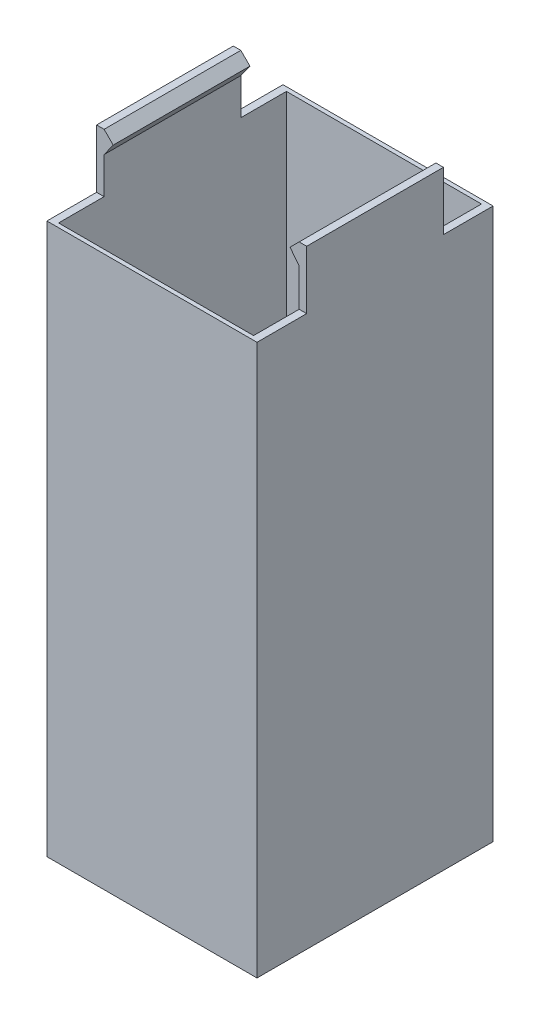
SolidWorks part; units mm, degrees
ref_plane "Front Plane" through (0, 0, 0) normal (0, 0, 1) x (1, 0, 0)
ref_plane "Top Plane" through (0, 0, 0) normal (0, 1, 0) x (1, 0, 0)
ref_plane "Right Plane" through (0, 0, 0) normal (1, 0, 0) x (0, 0, -1)
sketch "Sketch1" plane through (0, 0, 0) normal (0, 1, 0) x (1, 0, 0)
  line L0 (-23.05, 25.9) -> (42.3707, 25.9) construction
  line L1 (-23.05, 25.9) -> (23.05, 25.9)
  line L2 (-23.05, 25.9) -> (-23.05, -25.9)
  line L3 (-23.05, -25.9) -> (23.05, -25.9)
  line L4 (23.05, 25.9) -> (23.05, -25.9)
  line L5 (-23.05, 25.9) -> (23.05, -25.9) construction
  line L6 (-23.05, -25.9) -> (23.05, 25.9) construction
  line L7 (21.4, 25) -> (-21.4, 25)
  line L8 (21.4, 25) -> (21.4, -25)
  line L9 (21.4, -25) -> (-21.4, -25)
  line L10 (-21.4, 25) -> (-21.4, -25)
  line L11 (21.4, 25) -> (-21.4, -25) construction
  line L12 (21.4, -25) -> (-21.4, 25) construction
  point P0 (0, 0)
  point P6 (0, 0)
  dimension "D1" = 42.8
  dimension "D2" = 50
  dimension "D3" = 1.65
  dimension "D5" = 0.9
extrude "Boss-Extrude1" add sketch "Sketch1" along normal blind 120
sketch "Sketch2" plane through (0, 120, 0) normal (0, 1, 0) x (1, 0, 0)
  line L0 (-23.425, 0) -> (23.575, 0) construction
  line L1 (-23.05, 25.9) -> (-23.05, -25.9) construction
  line L3 (-21.4, 24.7662) -> (-21.4, -22.0296) construction
  line L4 (0, 23.9453) -> (0, -27.2839) construction
  line L5 (21.4, 15) -> (23.05, 15)
  line L6 (-21.4, -15) -> (-23.05, -15)
  line L7 (-21.4, -15) -> (-21.4, 15)
  line L8 (-21.4, 15) -> (-23.05, 15)
  line L9 (-23.05, -15) -> (-23.05, 15)
  line L10 (-21.4, -15) -> (-23.05, 15) construction
  line L11 (-21.4, 15) -> (-23.05, -15) construction
  line L12 (23.05, -15) -> (23.05, 15)
  line L13 (21.4, -15) -> (23.05, -15)
  line L14 (21.4, -15) -> (21.4, 15)
  line L15 (-21.4, 25) -> (-21.4, -25) construction
  point P11 (-22.225, 0)
  dimension "D2" = 30
  dimension "D3" = 25
extrude "Boss-Extrude2" add sketch "Sketch2" along normal blind 12.8
sketch "Sketch5" plane through (0, 0, 15) normal (0, 0, 1) x (1, 0, 0)
  line L0 (-19.4, 130.8) -> (19.4, 130.8) construction
  line L1 (21.4, 132.8) -> (21.4, 120) construction
  line L4 (-19.4, 130.8) -> (-21.4, 128)
  line L5 (-21.4, 128) -> (-21.4, 132.8)
  line L7 (-21.4, 132.8) -> (-19.4, 130.8)
  line L8 (21.4, 128.2) -> (21.4, 132.8)
  line L9 (19.4, 130.8) -> (21.4, 128.2)
  line L10 (21.4, 132.8) -> (19.4, 130.8)
  line L11 (-21.4, 132.8) -> (-21.4, 120) construction
  dimension "D1" = 10.8
  dimension "D2" = 2.8
  dimension "D3" = 2
  dimension "D4" = 2.6
  dimension "D5" = 2
extrude "Boss-Extrude5" add sketch "Sketch5" against normal up to surface (30 mm away) up to face at (22.225, 126.4, -15)
sketch "Sketch6" plane through (0, 0, 0) normal (0, -1, 0) x (1, 0, 0)
  line L0 (-23.05, 25.9) -> (23.05, 25.9) construction
  line L1 (23.05, 25.9) -> (-23.05, 25.9)
  line L2 (23.05, 25.9) -> (23.05, -25.9)
  line L3 (23.05, -25.9) -> (-23.05, -25.9)
  line L4 (-23.05, 25.9) -> (-23.05, -25.9)
extrude "Boss-Extrude6" add sketch "Sketch6" along normal blind 0.8
